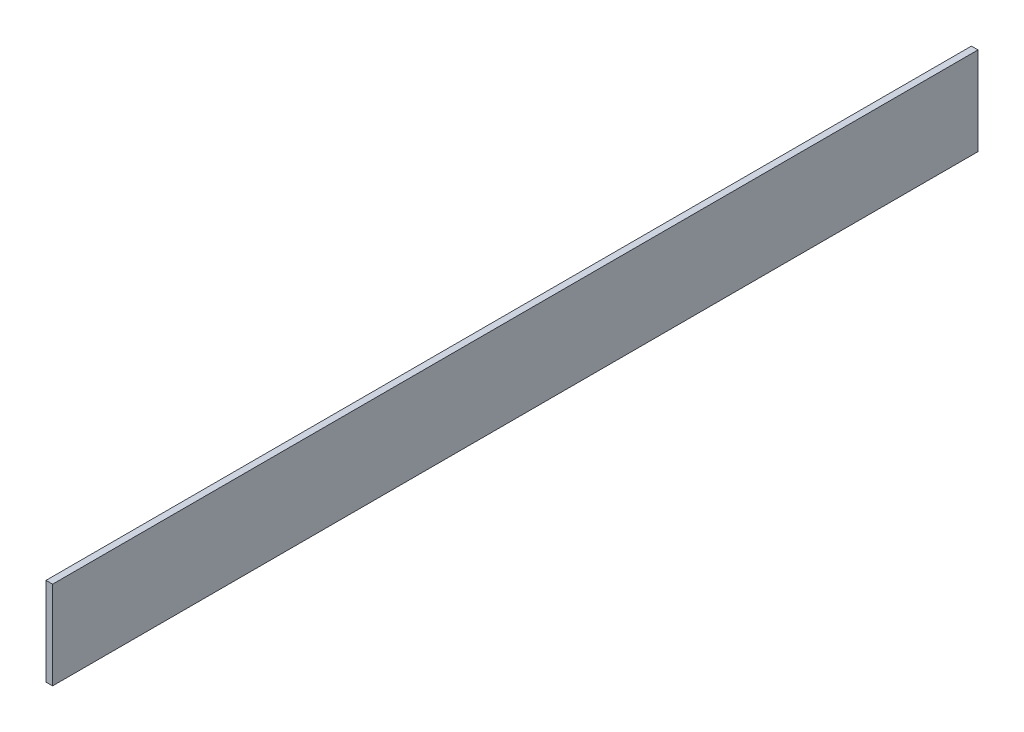
SolidWorks part; units mm, degrees
ref_plane "Ön Düzlem" through (0, 0, 0) normal (0, 0, 1) x (1, 0, 0)
ref_plane "Üst Düzlem" through (0, 0, 0) normal (0, 1, 0) x (1, 0, 0)
ref_plane "Sağ Düzlem" through (0, 0, 0) normal (1, 0, 0) x (0, 0, -1)
sketch "Sketch1" plane through (0, 0, 0) normal (1, 0, 0) x (0, 0, -1)
  line L1 (0, 0) -> (420, 0)
  line L2 (0, 0) -> (0, 40)
  line L3 (0, 40) -> (420, 40)
  line L4 (420, 0) -> (420, 40)
  dimension "D1" = 40
  dimension "D2" = 420
extrude "Boss-Extrude1" add sketch "Sketch1" along normal blind 3
